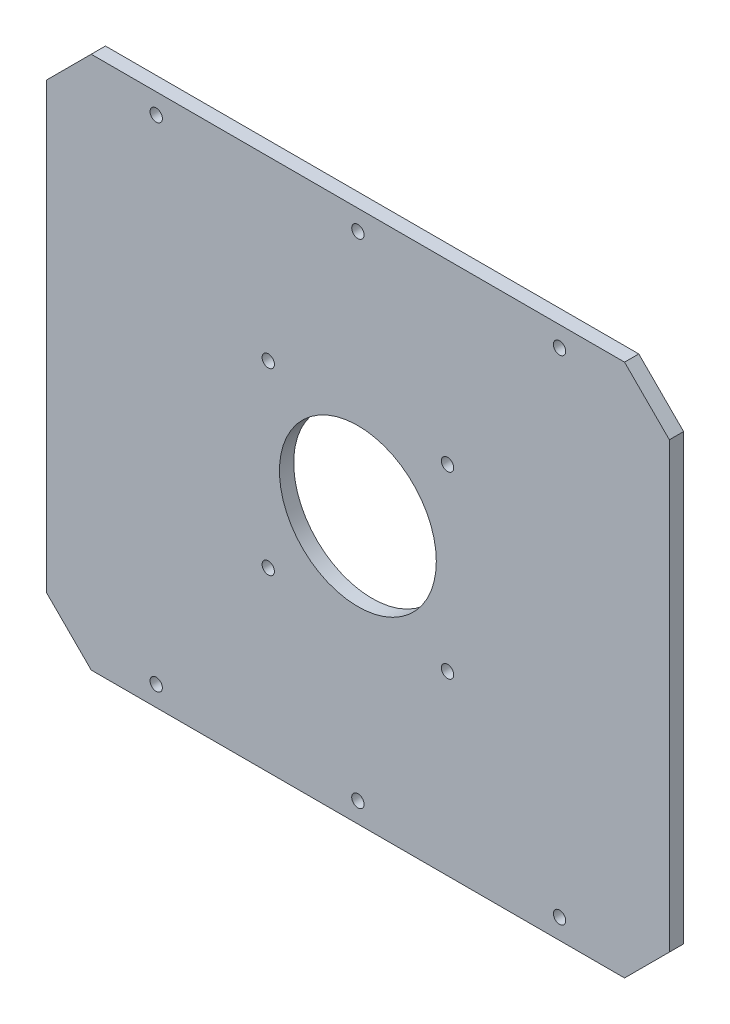
SolidWorks part; units mm, degrees
ref_plane "Front Plane" through (0, 0, 0) normal (0, 0, 1) x (1, 0, 0)
ref_plane "Top Plane" through (0, 0, 0) normal (0, 1, 0) x (1, 0, 0)
ref_plane "Right Plane" through (0, 0, 0) normal (1, 0, 0) x (0, 0, -1)
sketch "Sketch1" plane through (0, 0, 0) normal (0, 0, 1) x (1, 0, 0)
  line L0 (-79.0045, 0) -> (94.053, 0) construction
  line L1 (0, 67.0127) -> (0, -68.6587) construction
  line L3 (139, -119) -> (-139, -119)
  line L4 (139, -119) -> (139, 119)
  line L5 (139, 119) -> (-139, 119)
  line L6 (-139, -119) -> (-139, 119)
  line L7 (139, -119) -> (-139, 119) construction
  line L8 (139, 119) -> (-139, -119) construction
  point P4 (0, 0)
  dimension "D1" = 238
  dimension "D2" = 278
extrude "Boss-Extrude1" add sketch "Sketch1" along normal blind 6.35
sketch "Sketch2" plane through (0, 0, 6.35) normal (0, 0, 1) x (1, 0, 0)
  line L0 (-156.6091, 0) -> (177.3719, 0) construction
  line L1 (0, 110.6274) -> (0, -105.2428) construction
  circle A0 centre (0, 0) radius 35
  circle A1 centre (-40, 40) radius 2.75
  circle A2 centre (40, 40) radius 2.75
  circle A3 centre (40, -40) radius 2.75
  circle A4 centre (-40, -40) radius 2.75
  dimension "D1" = 40
  dimension "D2" = 5.5
  dimension "D3" = 70
  dimension "D4" = 40
extrude "Cut-Extrude1" cut sketch "Sketch2" against normal through all
chamfer "Chamfer1" distance 20 angle 45 4 edges at (139, -119, 3.175) (139, 119, 3.175) (-139, 119, 3.175) (-139, -119, 3.175)
sketch "Sketch4" plane through (0, 0, 6.35) normal (0, 0, 1) x (1, 0, 0)
  line L0 (0, 186.846) -> (0, -174.5938) construction
  line L1 (219.7737, 0) -> (-232.7917, 0) construction
  line L2 (119, 119) -> (-119, 119) construction
  line L3 (-90, 110) -> (0, 110) construction
  circle A0 centre (-90, 110) radius 2.75
  circle A1 centre (0, 110) radius 2.75
  circle A2 centre (90, 110) radius 2.75
  circle A3 centre (90, -110) radius 2.75
  circle A4 centre (0, -110) radius 2.75
  circle A5 centre (-90, -110) radius 2.75
  dimension "D1" = 5.5
  dimension "D2" = 9
  dimension "D3" = 90
extrude "Cut-Extrude2" cut sketch "Sketch4" against normal blind 76.2
equation "\"plate_thickness\" = 6.35 'thickness of the plate "
equation "\"height\"= 180"
equation "\"D1@Boss-Extrude1\"=\"plate_thickness\""
equation "\"t_height\" = 200"
equation "\"t_width\" = 240"
equation "\"t_length\" = 240"
equation "\"plate_spacing\" = 1"
equation "\"front_plate_height\" = \"t_height\" + 38"
equation "\"front_plate_width\" = \"t_width\" + 38"
equation "\"side_plate_height\" = \"front_plate_height\""
equation "\"side_plate_length\" = \"t_length\" + 38"
equation "\"top_plate_width\" = \"front_plate_width\""
equation "\"top_plate_length\" = \"side_plate_length\""
equation "\"D2@Sketch1\"=\"front_plate_width\""
equation "\"D1@Sketch1\"=\"front_plate_height\""
equation "\"plate_hole_spacing\"= 9"
equation "\"connector_D1\" = 70 'the big holes diameter"
equation "\"connector_mtg_D2\"= 5.5 'mounting holes"
equation "\"mtg_dfc\" = 40 'mounting hole distance from center"
equation "\"D3@Sketch2\"=\"connector_D1\""
equation "\"D2@Sketch2\"=\"mtg_hole_D\""
equation "\"D4@Sketch2\"=\"mtg_dfc\""
equation "\"D1@Sketch2\"=\"mtg_dfc\""
equation "\"mtg_hole_D\" = 5.5 'mounting holes"
equation "\"plate_hole_from_edge\" = 9"
equation "\"D1@Sketch4\"=\"mtg_hole_D\""
equation "\"D2@Sketch4\"=\"plate_hole_from_edge\""
equation "\"itx_support_t_slot_length\" = \"t_width\" + (2 * 20.5)"
equation "\"locomotion_length\" = \"t_length\""
equation "\"locomotion_width\" = \"t_width\""
equation "\"locomotion_height\" = 40"
equation "\"itx_mtg_hole_spacing\" = 40"
equation "\"emg30_bracket_hole_len\" = 60"
equation "\"emg30_bracket_hole_wid\" = 11"
